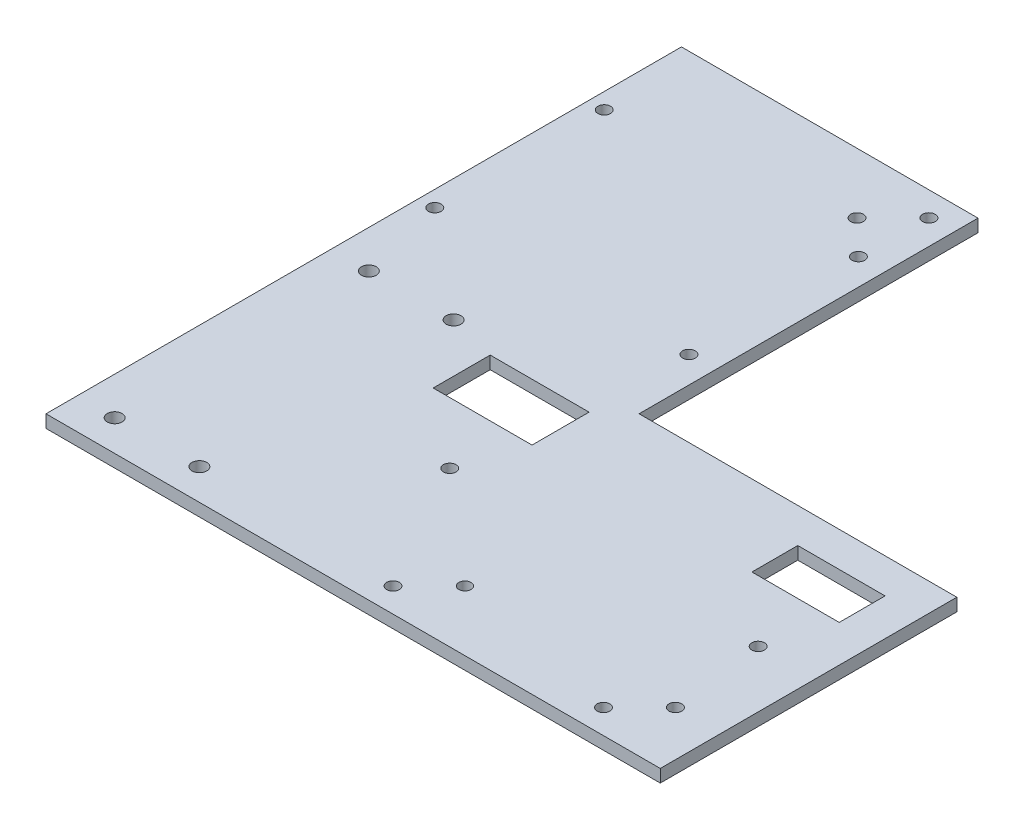
SolidWorks part; units mm, degrees
ref_plane "Front Plane" through (0, 0, 0) normal (0, 0, 1) x (1, 0, 0)
ref_plane "Top Plane" through (0, 0, 0) normal (0, 1, 0) x (1, 0, 0)
ref_plane "Right Plane" through (0, 0, 0) normal (1, 0, 0) x (0, 0, -1)
sketch "Sketch1" plane through (0, 0, 0) normal (0, 1, 0) x (1, 0, 0)
  line L0 (-72.5, -35) -> (72.5, -35)
  line L2 (-72.5, -35) -> (-72.5, 35)
  line L4 (72.5, -35) -> (72.5, 35)
  line L5 (-72.5, -35) -> (72.5, 35) construction
  line L6 (-72.5, 35) -> (72.5, -35) construction
  line L15 (-2.5, 35) -> (72.5, 35)
  line L17 (-72.5, 35) -> (-72.5, 115)
  line L18 (-72.5, 115) -> (-2.5, 115)
  line L19 (-2.5, 35) -> (-2.5, 115)
  line L20 (-15.9757, 22.7) -> (-42.5231, 22.7) construction
  line L21 (-32.0731, 15.9708) -> (-8.7404, 15.9708)
  line L22 (-32.0731, 15.9708) -> (-32.0731, 29.4292)
  line L23 (-32.0731, 29.4292) -> (-8.7404, 29.4292)
  line L24 (-8.7404, 15.9708) -> (-8.7404, 29.4292)
  line L25 (-32.0731, 15.9708) -> (-8.7404, 29.4292) construction
  line L26 (-32.0731, 29.4292) -> (-8.7404, 15.9708) construction
  line L27 (53.4675, -35) -> (53.4675, 115) construction
  line L28 (43.1642, 26.7968) -> (63.7708, 26.7968)
  line L29 (43.1642, 26.7968) -> (43.1642, 15.9708)
  line L30 (43.1642, 15.9708) -> (63.7708, 15.9708)
  line L31 (63.7708, 26.7968) -> (63.7708, 15.9708)
  line L32 (43.1642, 26.7968) -> (63.7708, 15.9708) construction
  line L33 (43.1642, 15.9708) -> (63.7708, 26.7968) construction
  circle A0 centre (3.6548, -29.2426) radius 1.5
  circle A1 centre (12.1401, -20.7574) radius 1.4446
  circle A2 centre (53.3381, -29.2426) radius 1.5
  circle A3 centre (61.8234, -20.7574) radius 1.5
  circle A4 centre (-16.8144, 100.7574) radius 1.5
  circle A5 centre (-8.3291, 109.2426) radius 1.5
  circle A6 centre (-13.6998, 1.5) radius 1.5
  circle A7 centre (59.1092, 1.5) radius 1.5
  circle A8 centre (-63.5846, -27.7106) radius 1.75
  circle A9 centre (-43.5846, -27.7106) radius 1.75
  circle A10 centre (-43.5846, 32.2894) radius 1.75
  circle A11 centre (-63.5846, 32.2894) radius 1.75
  circle A12 centre (-68.7404, 53.0097) radius 1.5
  circle A13 centre (-68.7404, 93.0097) radius 1.5
  circle A14 centre (-8.7404, 93.0097) radius 1.5
  circle A15 centre (-8.7404, 53.0097) radius 1.5
  point P0 (0, 0)
  point P57 (-20.4068, 22.7)
  point P64 (53.4675, 21.3838)
  dimension "D1" = 145
  dimension "D2" = 70
  dimension "D3" = 70
  dimension "D4" = 150
extrude "Boss-Extrude1" add sketch "Sketch1" along normal blind 3
